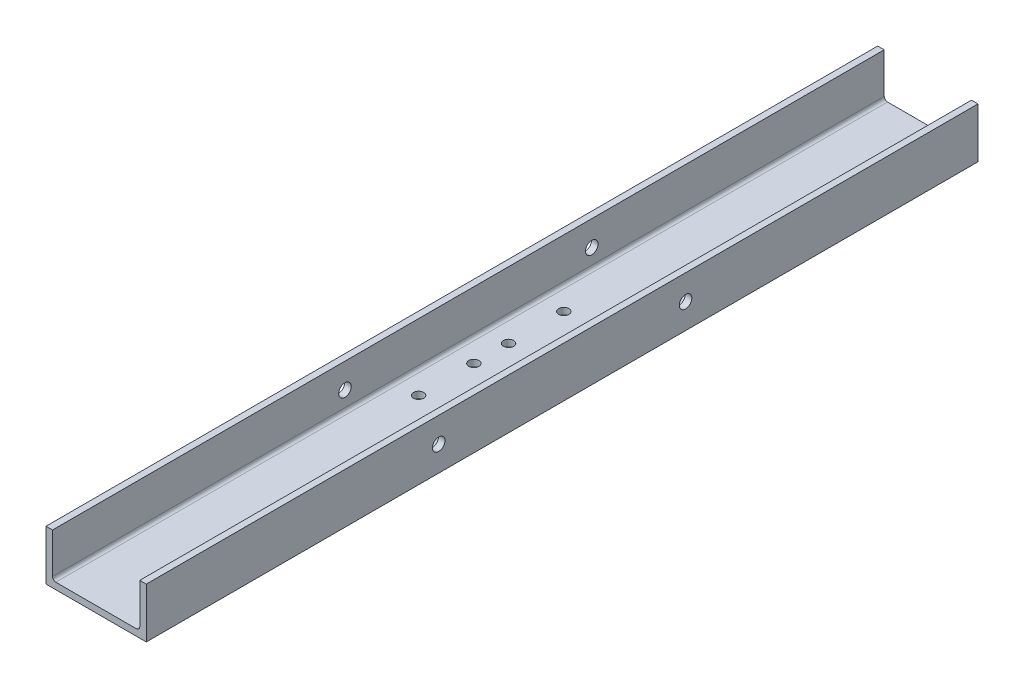
SolidWorks part; units mm, degrees
ref_plane "Front Plane" through (0, 0, 0) normal (0, 0, 1) x (1, 0, 0)
ref_plane "Top Plane" through (0, 0, 0) normal (0, 1, 0) x (1, 0, 0)
ref_plane "Right Plane" through (0, 0, 0) normal (1, 0, 0) x (0, 0, -1)
sketch "Sketch1" plane through (0, 0, 0) normal (0, 0, 1) x (1, 0, 0)
  line L0 (-25.4, 12.7) -> (-25.4, -12.7) construction
  line L1 (-25.4, -12.7) -> (25.4, -12.7) construction
  line L2 (25.4, -12.7) -> (25.4, 12.7) construction
  line L3 (22.098, -9.398) -> (-22.098, -9.398) construction
  line L4 (-22.098, -9.398) -> (-22.098, 12.7) construction
  line L6 (-22.098, 12.7) -> (-25.4, 12.7) construction
  line L7 (0, -12.7) -> (0, 0) construction
  line L8 (25.4, 12.7) -> (22.098, 12.7) construction
  line L9 (22.098, 12.7) -> (22.098, -9.398) construction
  line L10 (0, -9.398) -> (0, -12.7) construction
  point P4 (0, 0)
  point P11 (25.4, -9.398)
  dimension "Outside Height" = 25.4
  dimension "Outside Width" = 50.8
  dimension "Leg Thickness" = 3.302
  dimension "D1" = 12.7
  dimension "Inside Height" = 22.098
  dimension "Inside Width" = 44.196
  dimension "Base Thickness" = 3.302
sketch "Sketch2" plane through (0, 0, 0) normal (1, 0, 0) x (0, 0, -1)
  line L0 (210.695, 12.7) -> (-210.695, 12.7) construction
  line L1 (0, -9.398) -> (0, 12.7) construction
  point P0 (-159.895, 12.7)
  point P4 (0, 12.7)
  point P6 (159.895, 12.7)
  dimension "D1" = 50.8
  dimension "D2" = 50.8
  dimension "Length" = 421.39
sketch "Sketch3" plane through (0, 0, 0) normal (0, 0, 1) x (1, 0, 0)
  line L6 (-25.4, 12.7) -> (-25.4, -12.7)
  line L7 (-25.4, -12.7) -> (25.4, -12.7)
  line L8 (25.4, -12.7) -> (25.4, 12.7)
  line L9 (25.4, 12.7) -> (22.098, 12.7)
  line L10 (22.098, 12.7) -> (22.098, -9.398)
  line L11 (22.098, -9.398) -> (-22.098, -9.398)
  line L12 (-22.098, -9.398) -> (-22.098, 12.7)
  line L13 (-22.098, 12.7) -> (-25.4, 12.7)
extrude "Boss-Extrude1" add sketch "Sketch3" along normal mid plane 421.39
fillet "Fillet1" radius 1.651 2 edges at (22.098, -9.398, 0) (-22.098, -9.398, 0)
sketch "Sketch4" plane through (0, -9.398, 0) normal (0, 1, 0) x (1, 0, 0)
  line L0 (0, 210.695) -> (0, -210.695) construction
  line L1 (20.447, 210.695) -> (-20.447, 210.695) construction
  line L2 (20.447, -210.695) -> (-20.447, -210.695) construction
  line L3 (-23.5304, 0) -> (23.5304, 0) construction
  circle A0 centre (-10.5304, 8.79) radius 2.585
  circle A1 centre (10.4696, 8.79) radius 2.585
  circle A2 centre (-10.5304, 36.79) radius 2.585
  circle A3 centre (10.4696, 36.79) radius 2.585
  circle A4 centre (-10.5304, -36.79) radius 2.585
  circle A5 centre (10.4696, -36.79) radius 2.585
  circle A6 centre (10.4696, -8.79) radius 2.585
  circle A7 centre (-10.5304, -8.79) radius 2.585
  point P24 (0, 0)
  point P26 (0, 0)
  dimension "D1" = 5.17
  dimension "D2" = 5.17
  dimension "D3" = 28
  dimension "D4" = 8.79
  dimension "D5" = 8.79
  dimension "D6" = 28
extrude "Cut-Extrude1" cut sketch "Sketch4" against normal blind 10
sketch "Sketch5" plane through (0, -9.398, 0) normal (0, 1, 0) x (1, 0, 0)
  circle A0 centre (0, 62.5214) radius 3.18
  circle A2 centre (0, -62.52) radius 3.18
  circle A3 centre (-10.5304, -8.79) radius 2.585 construction
  dimension "D1" = 53.73
  dimension "D2" = 6.36
sketch "Sketch9" plane through (0, 0, 0) normal (1, 0, 0) x (0, 0, -1)
  line L0 (0, 0) -> (0, -12.7) construction
  line L1 (-210.695, -12.7) -> (210.695, -12.7) construction
  line L2 (0, 0) -> (-95.1707, 0) construction
  circle A0 centre (-62.52, 0) radius 3.18
  circle A1 centre (62.52, 0) radius 3.18
  point P8 (0, 0)
  dimension "D2" = 6.36
  dimension "D1" = 62.52
extrude "Cut-Extrude2" cut sketch "Sketch9" against normal mid plane 60
equation "\"D1@Boss-Extrude1\"=\"Length@Sketch2\""
equation "\"D2@Sketch2\"=\"D1@Sketch2\""
equation "\"D1@Sketch1\"=\"Outside Height@Sketch1\"/2"
equation "\"D1@Fillet1\"=\"Leg Thickness@Sketch1\"*.5"
equation "\"D1@Sketch2\"=\"Outside Width@Sketch1\"*1"
